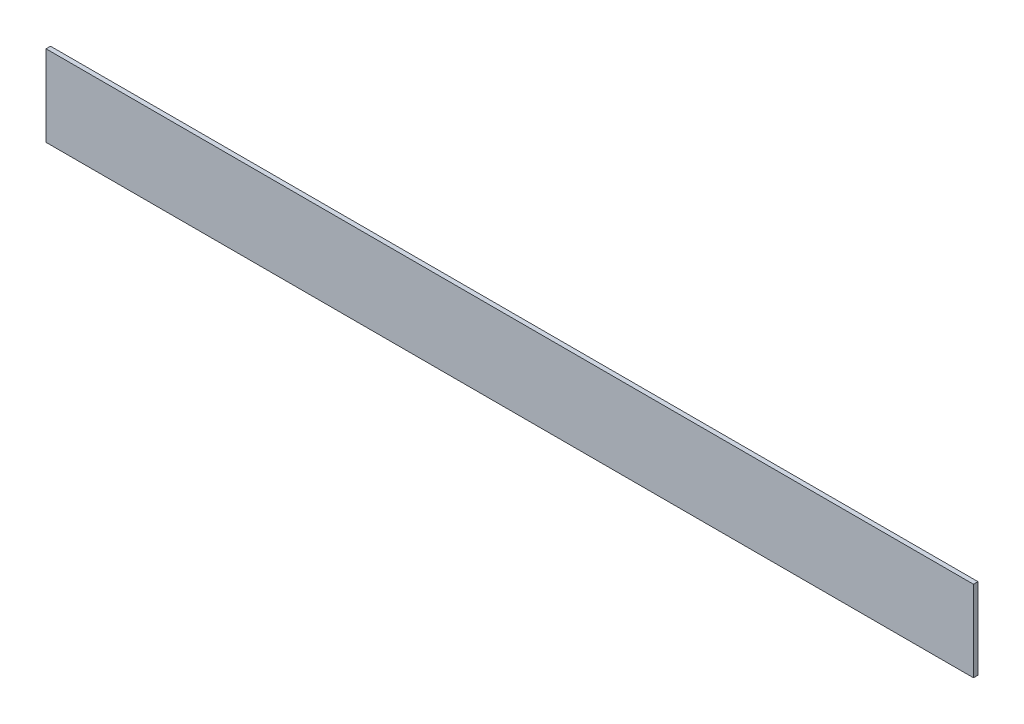
SolidWorks part; units mm, degrees
ref_plane "Front Plane" through (0, 0, 0) normal (0, 0, 1) x (1, 0, 0)
ref_plane "Top Plane" through (0, 0, 0) normal (0, 1, 0) x (1, 0, 0)
ref_plane "Right Plane" through (0, 0, 0) normal (1, 0, 0) x (0, 0, -1)
sketch "Sketch1" plane through (0, 0, 0) normal (0, 0, 1) x (1, 0, 0)
  line L1 (-327.025, 0) -> (327.025, 0)
  line L2 (-327.025, 0) -> (-327.025, 57.15)
  line L3 (-327.025, 57.15) -> (327.025, 57.15)
  line L4 (327.025, 0) -> (327.025, 57.15)
  line L5 (-327.025, 0) -> (327.025, 57.15) construction
  line L6 (-327.025, 57.15) -> (327.025, 0) construction
  point P4 (0, 28.575)
  point P5 (79.1084, 73.0977)
  dimension "D1" = 57.15
  dimension "D2" = 654.05
extrude "Boss-Extrude1" add sketch "Sketch1" along normal blind 3.175
